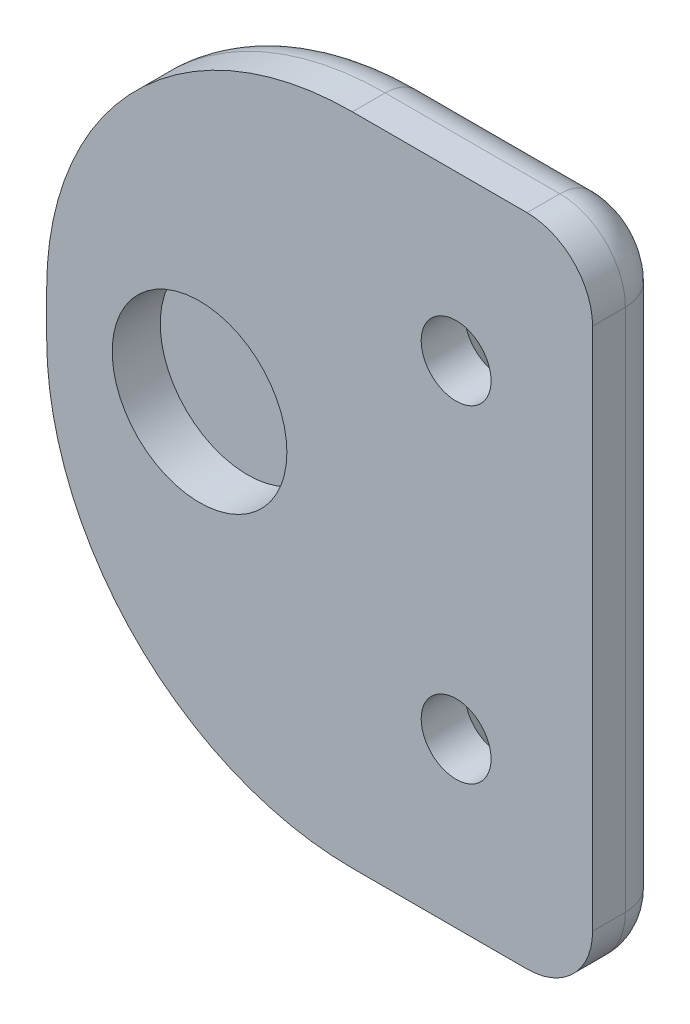
SolidWorks part; units mm, degrees
material "Настроенная пользователем пластмасса"
ref_plane "Front" through (0, 0, 0) normal (0, 0, 1) x (1, 0, 0)
ref_plane "Top" through (0, 0, 0) normal (0, 1, 0) x (1, 0, 0)
ref_plane "Right" through (0, 0, 0) normal (1, 0, 0) x (0, 0, -1)
sketch "Эскиз1" plane through (0, 0, 0) normal (0, 0, 1) x (1, 0, 0)
  line L0 (3.5, 36.1534) -> (3.5, -26.5132) construction
  line L1 (1.5, 15) -> (9.5, 15)
  line L2 (-12.5, 1) -> (-12.5, -1)
  line L3 (1.5, -15) -> (9.5, -15)
  line L4 (12.5, 12) -> (12.5, -12)
  line L5 (-12.5, 15) -> (12.5, -15) construction
  line L6 (-12.5, -15) -> (12.5, 15) construction
  line L7 (-27.3875, 0) -> (31.3196, 0) construction
  arc A0 (12.5, -12) -> (9.5, -15) centre (9.5, -12) cw
  arc A1 (12.5, 12) -> (9.5, 15) centre (9.5, 12) ccw
  arc A2 (-12.5, -1) -> (1.5, -15) centre (1.5, -1) ccw
  arc A3 (1.5, 15) -> (-12.5, 1) centre (1.5, 1) ccw
  circle A4 centre (6.25, 7.5) radius 1.6
  circle A5 centre (6.25, -7.5) radius 1.6
  point P0 (0, 0)
  dimension "D3" = 3
  dimension "D4" = 14
  dimension "D6" = 3.2
  dimension "D7" = 3.2
  dimension "D8" = 7.5
  dimension "D9" = 15
  dimension "D1" = 25
  dimension "D2" = 30
  dimension "D5" = 9
extrude "Бобышка-Вытянуть1" add sketch "Эскиз1" along normal blind 3.5
sketch "Эскиз2" plane through (0, 0, 3.5) normal (0, 0, 1) x (1, 0, 0)
  line L0 (-15.8774, 0) -> (14.1524, 0) construction
  line L1 (12.5, -12) -> (12.5, 12) construction
  circle A0 centre (-5.5, 0) radius 4
  dimension "D1" = 8
  dimension "D2" = 18
extrude "Вырез-Вытянуть1" cut sketch "Эскиз2" against normal blind 2.2
fillet "Скругление1" radius 2 8 edges at (11.6213, -14.1213, 0) (5.5, -15, 0) (-8.3995, -10.8995, 0) (-12.5, 0, 0) (-8.3995, 10.8995, 0) (5.5, 15, 0) (11.6213, 14.1213, 0) (12.5, 0, 0)
chamfer "Фаска1" distance 1.5 angle 45 2 edges at (7.85, -7.5, 0) (7.85, 7.5, 0)
